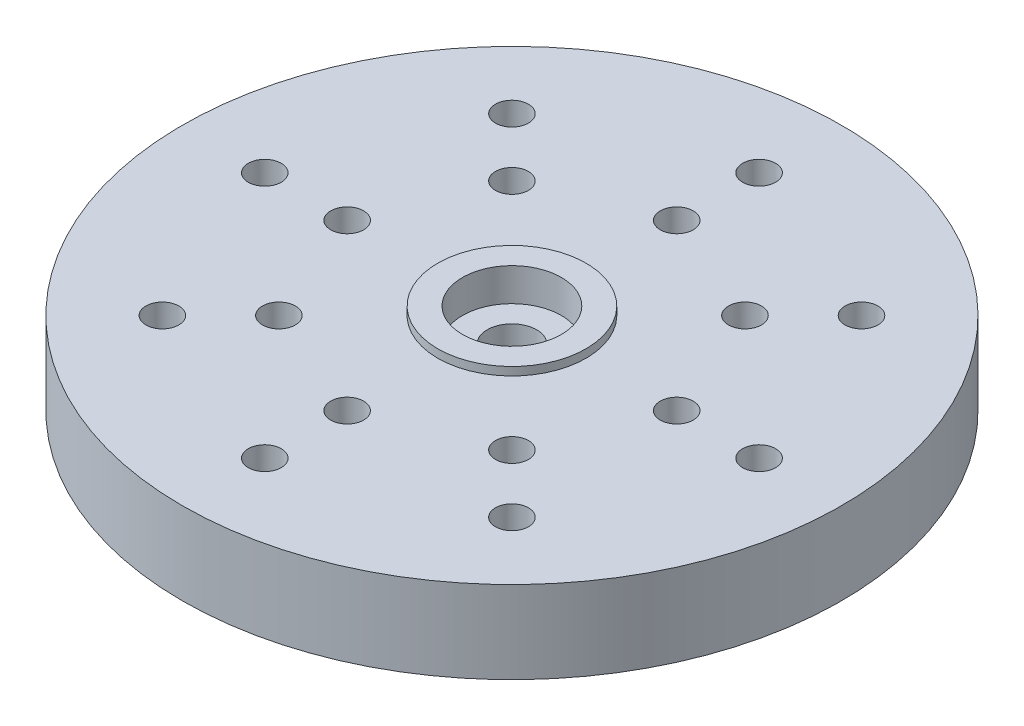
SolidWorks part; units mm, degrees
material "ABS"
ref_plane "Front Plane" through (0, 0, 0) normal (0, 0, 1) x (1, 0, 0)
ref_plane "Top Plane" through (0, 0, 0) normal (0, 1, 0) x (1, 0, 0)
ref_plane "Right Plane" through (0, 0, 0) normal (1, 0, 0) x (0, 0, -1)
sketch "Sketch1" plane through (0, 0, 0) normal (0, 1, 0) x (1, 0, 0)
  circle A0 centre (0, 0) radius 20
  dimension "D1" = 40
extrude "Boss-Extrude1" add sketch "Sketch1" along normal blind 5
sketch "Sketch3" plane through (0, 5, 0) normal (0, 1, 0) x (1, 0, 0)
  circle A0 centre (0, 15) radius 1
  circle A1 centre (0, 10) radius 1
  dimension "D1" = 5
  dimension "D2" = 10
  dimension "D3" = 2
  dimension "D4" = 2
extrude "Cut-Extrude2" cut sketch "Sketch3" against normal blind 10
pattern_circular "CirPattern1" count 8 over 360 about axis through (0, 0, 0) along (0, 1, 0) of "Cut-Extrude2"
sketch "Sketch5" plane through (0, 0, 0) normal (0, -1, 0) x (1, 0, 0)
  circle A0 centre (0, 0) radius 6
  dimension "D1" = 12
extrude "Boss-Extrude3" add sketch "Sketch5" along normal blind 3
sketch "Sketch8" plane through (0, -3, 0) normal (0, -1, 0) x (1, 0, 0)
  line L0 (0, 3.75) -> (0, 3.05) construction
  line L1 (0, 3.05) -> (0.7, 3.6841)
  line L2 (0, 3.05) -> (-0.7, 3.6841)
  line L3 (1.2405, 2.7863) -> (2.1379, 3.0809)
  line L4 (1.2405, 2.7863) -> (0.859, 3.6503)
  line L5 (2.2666, 2.0408) -> (3.2062, 1.9449)
  line L6 (2.2666, 2.0408) -> (2.2694, 2.9853)
  line L7 (2.9007, 0.9425) -> (3.7201, 0.4727)
  line L8 (2.9007, 0.9425) -> (3.2875, 1.8042)
  line L9 (3.0333, -0.3188) -> (3.5907, -1.0813)
  line L10 (3.0333, -0.3188) -> (3.7371, 0.3111)
  line L11 (2.6414, -1.525) -> (2.8405, -2.4483)
  line L12 (2.6414, -1.525) -> (3.5405, -1.2358)
  line L13 (1.7927, -2.4675) -> (1.5991, -3.3919)
  line L14 (1.7927, -2.4675) -> (2.7318, -2.569)
  line L15 (0.6341, -2.9834) -> (0.0813, -3.7491)
  line L16 (0.6341, -2.9834) -> (1.4507, -3.458)
  line L17 (-0.6341, -2.9834) -> (-1.4507, -3.458)
  line L18 (-0.6341, -2.9834) -> (-0.0813, -3.7491)
  line L19 (-1.7927, -2.4675) -> (-2.7318, -2.569)
  line L20 (-1.7927, -2.4675) -> (-1.5991, -3.3919)
  line L21 (-2.6414, -1.525) -> (-3.5405, -1.2358)
  line L22 (-2.6414, -1.525) -> (-2.8405, -2.4483)
  line L23 (-3.0333, -0.3188) -> (-3.7371, 0.3111)
  line L24 (-3.0333, -0.3188) -> (-3.5907, -1.0813)
  line L25 (-2.9007, 0.9425) -> (-3.2875, 1.8042)
  line L26 (-2.9007, 0.9425) -> (-3.7201, 0.4727)
  line L27 (-2.2666, 2.0408) -> (-2.2694, 2.9853)
  line L28 (-2.2666, 2.0408) -> (-3.2062, 1.9449)
  line L29 (-1.2405, 2.7863) -> (-0.859, 3.6503)
  line L30 (-1.2405, 2.7863) -> (-2.1379, 3.0809)
  circle A0 centre (0, 0) radius 3.75 construction
  arc A1 (-0.7, 3.6841) -> (0.7, 3.6841) centre (0, 0) cw construction
  arc A2 (0.7, 3.6841) -> (0.9, 3.6404) centre (0, 0) cw
  arc A3 (2.1379, 3.0809) -> (2.3029, 2.9596) centre (0, 0) cw
  arc A4 (3.2062, 1.9449) -> (3.3076, 1.7671) centre (0, 0) cw
  arc A5 (3.7201, 0.4727) -> (3.7403, 0.269) centre (0, 0) cw
  arc A6 (3.5907, -1.0813) -> (3.5264, -1.2756) centre (0, 0) cw
  arc A7 (2.8405, -2.4483) -> (2.7027, -2.5996) centre (0, 0) cw
  arc A8 (1.5991, -3.3919) -> (1.4117, -3.4742) centre (0, 0) cw
  arc A9 (0.0813, -3.7491) -> (-0.1235, -3.748) centre (0, 0) cw
  arc A10 (-1.4507, -3.458) -> (-1.6372, -3.3737) centre (0, 0) cw
  arc A11 (-2.7318, -2.569) -> (-2.8679, -2.4161) centre (0, 0) cw
  arc A12 (-3.5405, -1.2358) -> (-3.6027, -1.0408) centre (0, 0) cw
  arc A13 (-3.7371, 0.3111) -> (-3.7145, 0.5145) centre (0, 0) cw
  arc A14 (-3.2875, 1.8042) -> (-3.1841, 1.9809) centre (0, 0) cw
  arc A15 (-2.2694, 2.9853) -> (-2.1031, 3.1047) centre (0, 0) cw
  arc A16 (-0.859, 3.6503) -> (-0.6585, 3.6917) centre (0, 0) cw
  point P64 (0, 0)
extrude "Cut-Extrude5" cut sketch "Sketch8" against normal through all contours A16 L29 L30 A15 L27 L28 A14 L25 L26 A13 L23 L24 A12 L21 L22 A11 L19 L20 A10 L17 L18 A9 L15 L16 A8 L13 L14 A7 L11 L12 A6 L9 L10 A5 L7 L8 A4 L5 L6 A3 L3 L4 A2 L1 L2
sketch "Sketch4" plane through (0, 5, 0) normal (0, 1, 0) x (1, 0, 0)
  circle A0 centre (0, 0) radius 4.5
  dimension "D1" = 9
extrude "Boss-Extrude4" add sketch "Sketch4" along normal blind 0.5 and the other way blind 4.96
sketch "Sketch10" plane through (0, 5.5, 0) normal (0, 1, 0) x (1, 0, 0)
  circle A0 centre (0, 0) radius 3
  dimension "D1" = 6
extrude "Cut-Extrude6" cut sketch "Sketch10" against normal blind 2
sketch "Sketch11" plane through (0, 3.5, 0) normal (0, 1, 0) x (1, 0, 0)
  circle A0 centre (0, 0) radius 1.5
  dimension "D1" = 3
extrude "Cut-Extrude7" cut sketch "Sketch11" against normal through all
